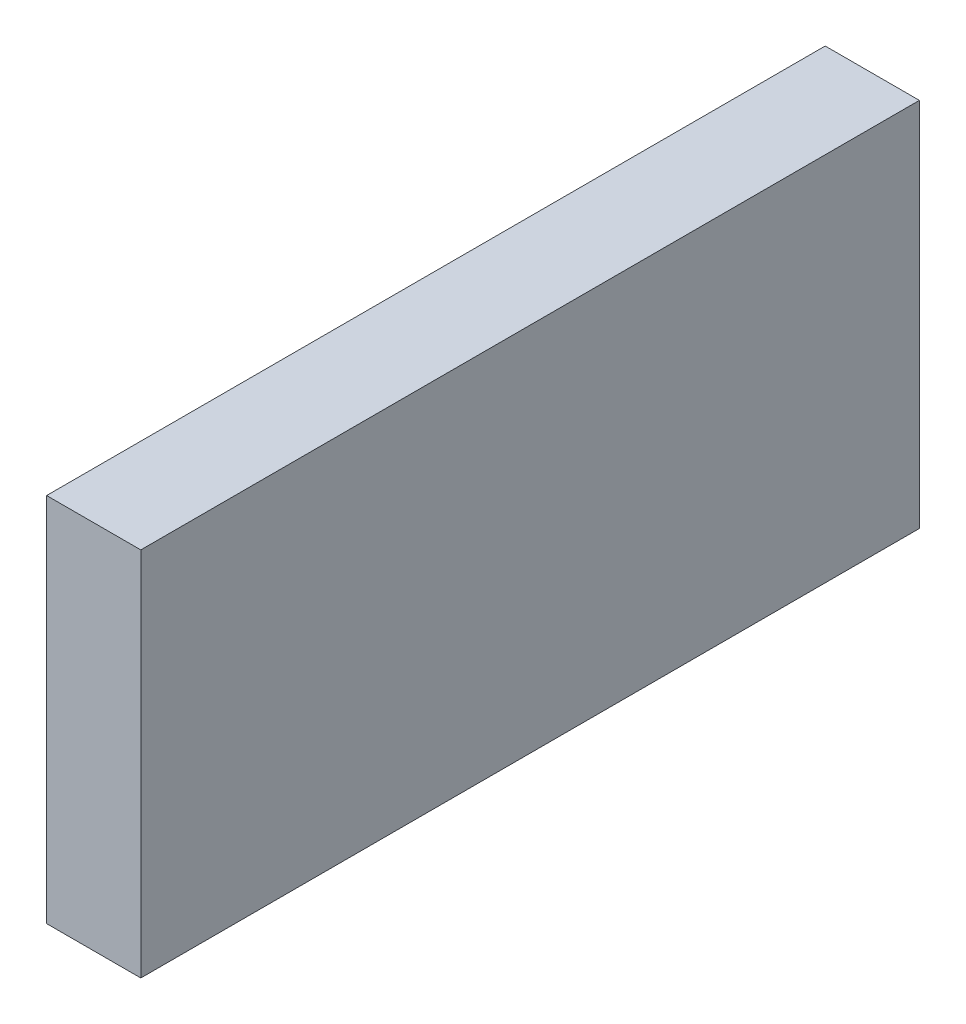
SolidWorks part; units mm, degrees
ref_plane "Front Plane" through (0, 0, 0) normal (0, 0, 1) x (1, 0, 0)
ref_plane "Top Plane" through (0, 0, 0) normal (0, 1, 0) x (1, 0, 0)
ref_plane "Right Plane" through (0, 0, 0) normal (1, 0, 0) x (0, 0, -1)
sketch "Sketch1" plane through (0, 0, 0) normal (1, 0, 0) x (0, 0, -1)
  line L1 (-30.5891, 18.2069) -> (11.4109, 18.2069)
  line L2 (-30.5891, 18.2069) -> (-30.5891, -1.7931)
  line L3 (-30.5891, -1.7931) -> (11.4109, -1.7931)
  line L4 (11.4109, 18.2069) -> (11.4109, -1.7931)
  dimension "D1" = 42
  dimension "D2" = 20
extrude "Boss-Extrude1" add sketch "Sketch1" along normal blind 5.08
